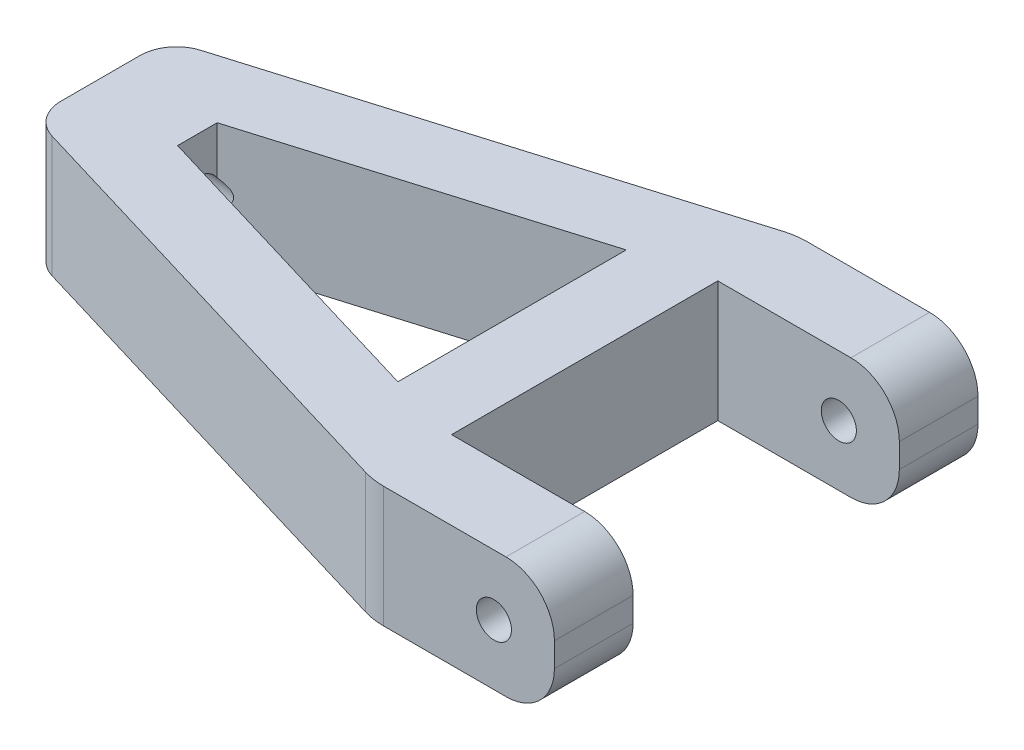
SolidWorks part; units mm, degrees
ref_plane "Front" through (0, 0, 0) normal (0, 0, 1) x (1, 0, 0)
ref_plane "Top" through (0, 0, 0) normal (0, 1, 0) x (1, 0, 0)
ref_plane "Right" through (0, 0, 0) normal (1, 0, 0) x (0, 0, -1)
sketch "Sketch1" plane through (0, 0, 0) normal (0, 1, 0) x (1, 0, 0)
  line L1 (0, 0) -> (55, 0)
  line L2 (0, 0) -> (0, -35)
  line L3 (0, -35) -> (55, -35)
  line L4 (55, 0) -> (55, -35)
  dimension "D1" = 35
  dimension "D2" = 55
extrude "Boss-Extrude1" add sketch "Sketch1" along normal blind 10
sketch "Sketch2" plane through (55, 0, 0) normal (1, 0, 0) x (0, 0, -1)
  line L0 (-35, 10) -> (0, 10) construction
  line L1 (-28.5, 10) -> (-6.5, 10)
  line L2 (-28.5, 10) -> (-28.5, 0)
  line L3 (-28.5, 0) -> (-6.5, 0)
  line L4 (-6.5, 10) -> (-6.5, 0)
  line L5 (-35, 0) -> (0, 0) construction
  line L6 (-35, 10) -> (-35, 0) construction
  line L7 (0, 10) -> (0, 0) construction
  dimension "D1" = 6.5
  dimension "D2" = 6.5
sketch "Sketch9" plane through (0, 0, 0) normal (0, -1, 0) x (-1, 0, 0)
  line L0 (0, -12) -> (-40, 0)
  line L1 (0, 0) -> (0, -35) construction
  line L2 (-55, 0) -> (0, 0) construction
  line L3 (-40, 0) -> (0, 0)
  line L4 (0, 0) -> (0, -12)
  line L5 (0, -23) -> (-40, -35)
  line L6 (0, -35) -> (-55, -35) construction
  line L7 (-40, -35) -> (0, -35)
  line L8 (0, -35) -> (0, -23)
  dimension "D1" = 12
  dimension "D2" = 12
  dimension "D3" = 40
  dimension "D4" = 40
extrude "Cut-Extrude6" cut sketch "Sketch9" against normal through all
sketch "Sketch12" plane through (0, 0, 35) normal (0, 0, 1) x (1, 0, 0)
  line L0 (55, 10) -> (55, 0) construction
  line L2 (18, 0) -> (55, 0) construction
  circle A0 centre (50, 5) radius 1.45
  dimension "D1" = 2.9
  dimension "D2" = 5
  dimension "D3" = 5
extrude "Cut-Extrude8" cut sketch "Sketch12" against normal through all
sketch "Sketch13" plane through (0, 0, 0) normal (-1, 0, 0) x (0, 0, 1)
  circle A0 centre (17.5, 5) radius 1.95
  dimension "D1" = 3.9
extrude "Cut-Extrude9" cut sketch "Sketch13" against normal blind 11
extrude "Cut-Extrude10" cut sketch "Sketch2" against normal blind 15
fillet "Fillet4" radius 4 4 edges at (55, 10, 31.75) (55, 0, 31.75) (55, 10, 3.25) (55, 0, 3.25)
fillet "Fillet5" radius 3 2 edges at (0, 5, 12) (0, 5, 23)
fillet "Fillet6" radius 6 2 edges at (40, 5, 35) (40, 5, 0)
sketch "Sketch15" plane through (0, 0, 0) normal (0, -1, 0) x (-1, 0, 0)
  line L0 (-34, -26.9358) -> (-8, -19.1358)
  line L1 (-8, -19.1358) -> (-8, -15.8642)
  line L2 (-8, -15.8642) -> (-34, -8.0642)
  line L3 (-34, -8.0642) -> (-34, -26.9358)
  line L4 (0, -14.2321) -> (0, -20.7679) construction
  line L5 (-2.138, -23.6414) -> (-39.1565, -34.747) construction
  line L6 (-39.1565, -0.253) -> (-2.138, -11.3586) construction
  line L7 (-40, -28.5) -> (-40, -6.5) construction
  dimension "D1" = 8
  dimension "D2" = 6
  dimension "D3" = 6
  dimension "D4" = 6
  dimension "D5" = 6
  dimension "D6" = 6
extrude "Cut-Extrude11" cut sketch "Sketch15" against normal through all
